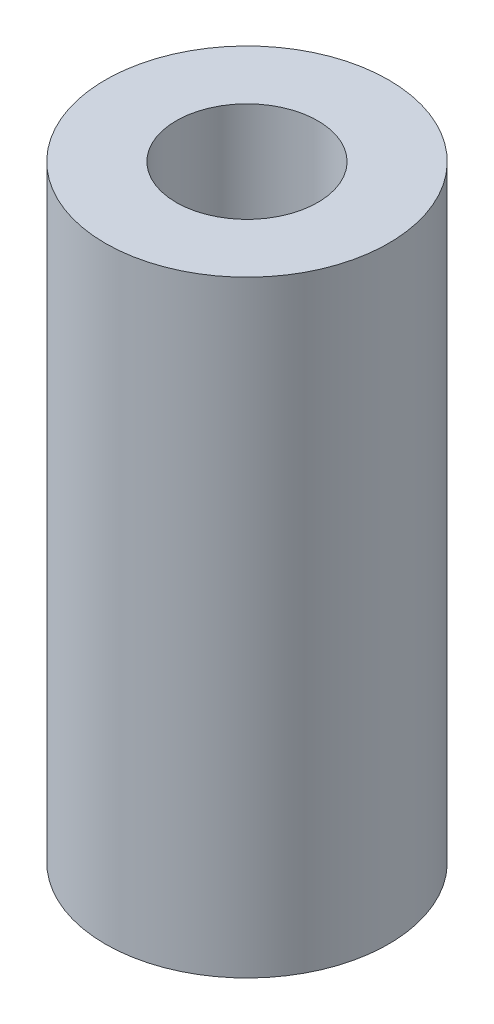
SolidWorks part; units mm, degrees
ref_plane "Front Plane" through (0, 0, 0) normal (0, 0, 1) x (1, 0, 0)
ref_plane "Top Plane" through (0, 0, 0) normal (0, 1, 0) x (1, 0, 0)
ref_plane "Right Plane" through (0, 0, 0) normal (1, 0, 0) x (0, 0, -1)
sketch "Sketch1" plane through (0, 0, 0) normal (0, 1, 0) x (1, 0, 0)
  circle A0 centre (0, 0) radius 3.5
  circle A1 centre (0, 0) radius 1.75
  dimension "D1" = 7
  dimension "D2" = 3.5
extrude "Boss-Extrude1" add sketch "Sketch1" along normal blind 15
sketch "Sketch2" plane through (0, 15, 0) normal (0, 1, 0) x (1, 0, 0)
  circle A0 centre (0, 0) radius 2
  dimension "D1" = 4
extrude "Cut-Extrude1" [suppressed] cut sketch "Sketch2" against normal blind 10
